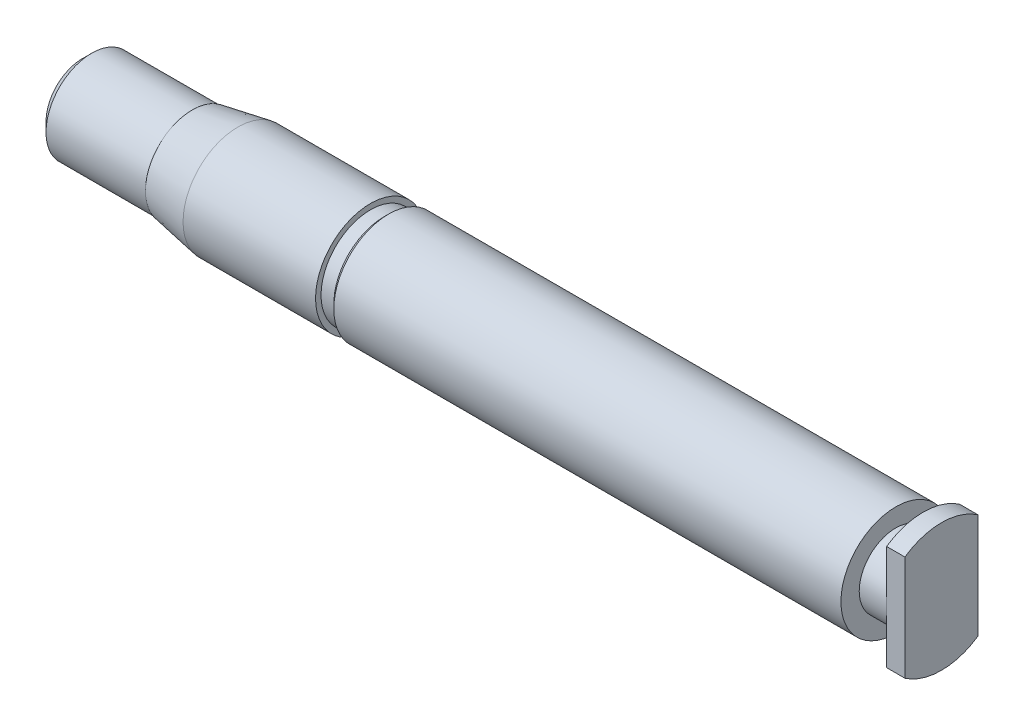
SolidWorks part; units mm, degrees
ref_plane "Plan de face" through (0, 0, 0) normal (0, 0, 1) x (1, 0, 0)
ref_plane "Plan de dessus" through (0, 0, 0) normal (0, 1, 0) x (1, 0, 0)
ref_plane "Plan de droite" through (0, 0, 0) normal (1, 0, 0) x (0, 0, -1)
sketch "Esquisse1" plane through (0, 0, 0) normal (0, 0, 1) x (1, 0, 0)
  line L0 (0, 0) -> (90.0796, 0) construction
  line L1 (0, 0) -> (0, 5)
  line L2 (0, 5) -> (12, 5)
  line L3 (12, 5) -> (12, 5.1184)
  line L4 (12, 5.1184) -> (17, 6)
  line L5 (17, 6) -> (31.5, 6)
  line L10 (31.5, 6) -> (31.5, 5.4)
  line L11 (31.5, 5.4) -> (33, 5.4)
  line L12 (33, 5.4) -> (33, 6)
  line L13 (33, 6) -> (89, 6)
  line L14 (89, 6) -> (89, 4)
  line L15 (89, 4) -> (92, 4)
  line L16 (92, 4) -> (92, 7)
  line L17 (92, 7) -> (94, 7)
  line L18 (94, 7) -> (94, 0)
  line L20 (94, 0) -> (0, 0)
  dimension "D1" = 5
  dimension "D2" = 5
  dimension "D3" = 6
  dimension "D4" = 12
  dimension "D5" = 10
  dimension "D6" = 89
  dimension "D10" = 5.4
  dimension "D11" = 1.5
  dimension "D12" = 6
  dimension "D13" = 4
  dimension "D14" = 7
  dimension "D15" = 3
  dimension "D16" = 2
  dimension "D17" = 57.5
revolve "Révolution1" add sketch "Esquisse1" angle 360 about L0
cosmetic thread "Représentation de filetage2" parameters "D2"=8.5
chamfer "Chanfrein1" distance 1 angle 45 1 edges at (0, 0, 5)
chamfer "Chanfrein2" distance 0.5 angle 45 1 edges at (33, 0, 6)
sketch "Esquisse2" plane through (94, 0, 0) normal (1, 0, 0) x (0, 0, -1)
  line L0 (0, 7.5482) -> (0, -7.4621) construction
  line L1 (-4, 7.5482) -> (-4, -7.7204)
  line L2 (4, 7.5482) -> (9.1374, 7.5482)
  line L3 (4, 7.5482) -> (4, -7.7204)
  line L4 (4, -7.7204) -> (9.1374, -7.7204)
  line L5 (9.1374, 7.5482) -> (9.1374, -7.7204)
  line L6 (-4, 7.5482) -> (-9.1374, 7.5482)
  line L7 (-9.1374, 7.5482) -> (-9.1374, -7.7204)
  line L8 (-4, -7.7204) -> (-9.1374, -7.7204)
  dimension "D1" = 8
extrude "Enlèv. mat.-Extru.1" cut sketch "Esquisse2" against normal up to next
